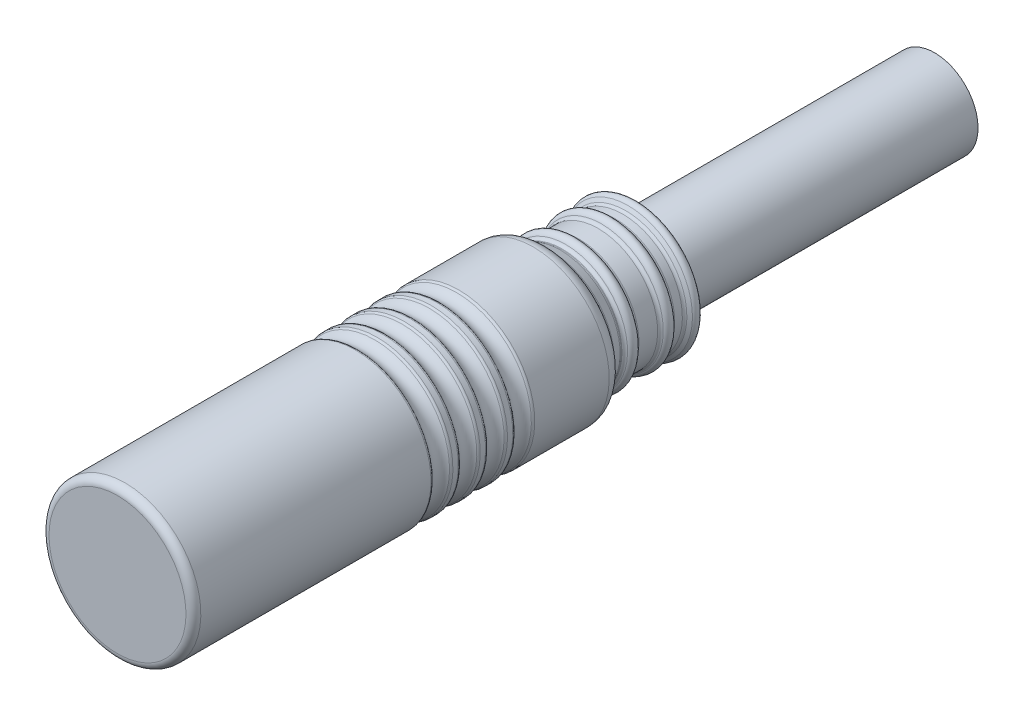
SolidWorks part; units mm, degrees
ref_plane "Front Plane" through (0, 0, 0) normal (0, 0, 1) x (1, 0, 0)
ref_plane "Top Plane" through (0, 0, 0) normal (0, 1, 0) x (1, 0, 0)
ref_plane "Right Plane" through (0, 0, 0) normal (1, 0, 0) x (0, 0, -1)
sketch "Sketch1" plane through (0, 0, 0) normal (1, 0, 0) x (0, 0, -1)
  line L0 (0, 0) -> (0, 4.6)
  line L1 (0.5, 5.1) -> (27.9386, 5.1)
  line L2 (28.7923, 4.6207) -> (28.8923, 4.4568)
  line L3 (29.141, 4.25) -> (29.7532, 4.0164)
  line L4 (29.8423, 4) -> (29.8923, 4)
  line L5 (34.155, 4.1021) -> (34.313, 4.3173)
  line L6 (34.9, 4.125) -> (34.9, 0)
  line L7 (34.9, 0) -> (0, 0)
  line L10 (31.038, 4) -> (32.2923, 4)
  line L11 (33.438, 4) -> (33.9535, 4)
  arc A1 (0, 4.6) -> (0.5, 5.1) centre (0.5, 4.6) cw
  arc A2 (27.9386, 5.1) -> (28.7923, 4.6207) centre (27.9386, 4.1) cw
  arc A3 (30.8088, 4.15) -> (30.1215, 4.15) centre (30.4652, 4) ccw
  arc A4 (33.2088, 4.15) -> (32.5215, 4.15) centre (32.8652, 4) ccw
  arc A6 (34.313, 4.3173) -> (34.9, 4.125) centre (34.575, 4.125) cw
  arc A7 (33.2088, 4.15) -> (33.438, 4) centre (33.438, 4.25) ccw
  arc A8 (30.8088, 4.15) -> (31.038, 4) centre (31.038, 4.25) ccw
  arc A9 (30.1215, 4.15) -> (29.8923, 4) centre (29.8923, 4.25) cw
  arc A10 (29.7532, 4.0164) -> (29.8423, 4) centre (29.8423, 4.25) ccw
  arc A11 (33.9535, 4) -> (34.155, 4.1021) centre (33.9535, 4.25) ccw
  arc A12 (32.5215, 4.15) -> (32.2923, 4) centre (32.2923, 4.25) cw
  arc A13 (28.8923, 4.4568) -> (29.141, 4.25) centre (29.3192, 4.7172) ccw
  arc A14 (21.6185, 5.0263) -> (22.7815, 5.0263) centre (22.2, 5.5) ccw
  arc A15 (22.9365, 5.1) -> (22.7815, 5.0263) centre (22.9365, 4.9) ccw
  arc A16 (21.6185, 5.0263) -> (21.4635, 5.1) centre (21.4635, 4.9) ccw
  arc A17 (19.7852, 5.0263) -> (19.6301, 5.1) centre (19.6301, 4.9) ccw
  arc A18 (19.7852, 5.0263) -> (20.9482, 5.0263) centre (20.3667, 5.5) ccw
  arc A19 (21.1032, 5.1) -> (20.9482, 5.0263) centre (21.1032, 4.9) ccw
  arc A20 (17.9518, 5.0263) -> (17.7968, 5.1) centre (17.7968, 4.9) ccw
  arc A21 (17.9518, 5.0263) -> (19.1148, 5.0263) centre (18.5333, 5.5) ccw
  arc A22 (19.2699, 5.1) -> (19.1148, 5.0263) centre (19.2699, 4.9) ccw
  arc A23 (16.1185, 5.0263) -> (15.9635, 5.1) centre (15.9635, 4.9) ccw
  arc A24 (16.1185, 5.0263) -> (17.2815, 5.0263) centre (16.7, 5.5) ccw
  arc A25 (17.4365, 5.1) -> (17.2815, 5.0263) centre (17.4365, 4.9) ccw
  point P0 (23.0212, 5.5)
  point P11 (0.5, 0.4705)
  point P16 (0, 5.1)
  point P19 (28.5, 5.1)
  point P26 (7.755, 4.815)
  point P29 (34.575, 4.45)
  point P30 (32.8652, 4.375)
  point P33 (22.2, 4.75)
  point P40 (33.2402, 4)
  point P43 (30.8402, 4)
  point P54 (32.4902, 4)
  point P76 (8.37, 0)
  point P77 (0.5, 0)
  dimension "D6" = 0.5
  dimension "D7" = 1
  dimension "D9" = 0.25
  dimension "D12" = 0.25
  dimension "D11" = 0.375
  dimension "D13" = 0.5
  dimension "D15" = 1
  dimension "D18" = 0.325
  dimension "D21" = 0.75
  dimension "D22" = 0.2
  dimension "D3" = 5.1
  dimension "D4" = 34.9
  dimension "D5" = 28.5
  dimension "D8" = 4
  dimension "D10" = 4.45
  dimension "D14" = 0.1
  dimension "D16" = 2.4
  dimension "D17" = 0.05
  dimension "D20" = 5.5
  dimension "D23" = 4.75
  dimension "D24" = 16.7
  dimension "D19" = 4
revolve "Revolve1" add sketch "Sketch1" angle 360 about L7
sketch "Sketch2" plane through (0, 0, -34.9) normal (0, 0, -1) x (-1, 0, 0)
  circle A0 centre (0, 0) radius 2.92
extrude "Boss-Extrude1" add sketch "Sketch2" along normal blind 20
